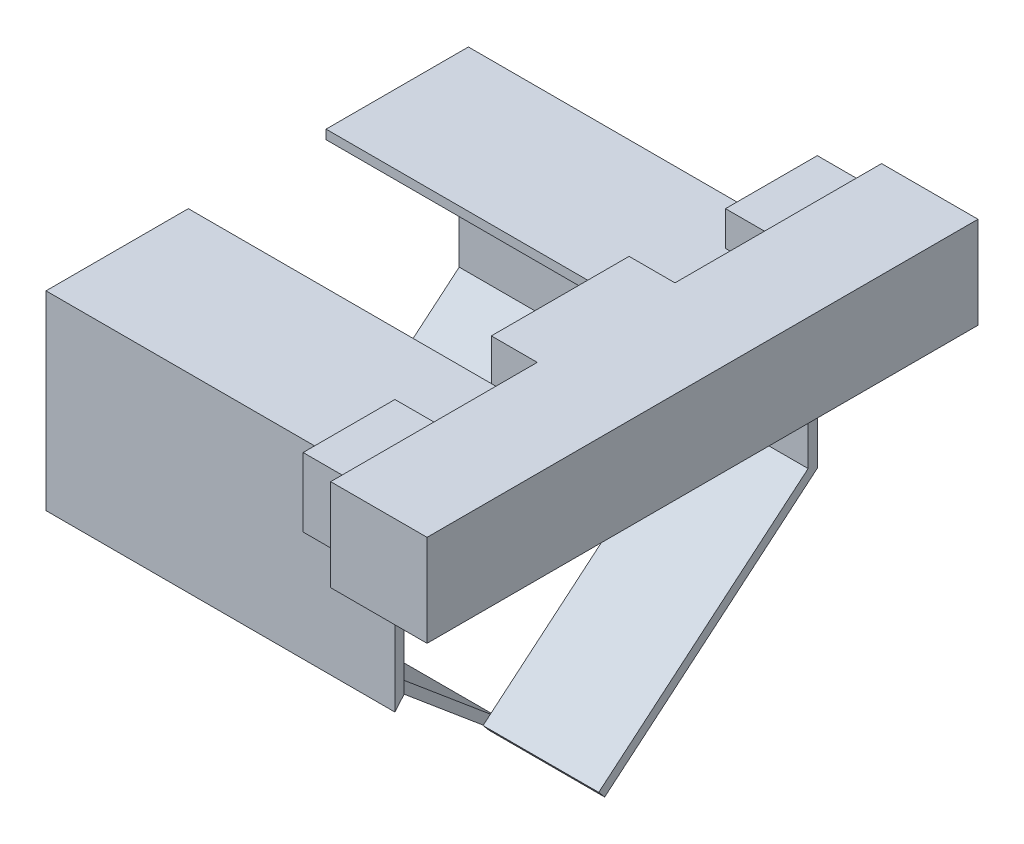
SolidWorks part; units mm, degrees
ref_plane "Front Plane" through (0, 0, 0) normal (0, 0, 1) x (1, 0, 0)
ref_plane "Top Plane" through (0, 0, 0) normal (0, 1, 0) x (1, 0, 0)
ref_plane "Right Plane" through (0, 0, 0) normal (1, 0, 0) x (0, 0, -1)
sketch "Sketch1" plane through (0, 0, 0) normal (1, 0, 0) x (0, 0, -1)
  line L0 (-19.05, 0) -> (19.05, 0) construction
  line L1 (19.05, 0) -> (57.15, 0)
  line L2 (57.15, 0) -> (57.15, -50.8)
  line L3 (57.15, -50.8) -> (-1.2226, -99.7804)
  line L4 (-19.05, 0) -> (-57.15, 0)
  line L5 (-57.15, 0) -> (-57.15, -50.8)
  line L6 (-57.15, -50.8) -> (1.2226, -99.7804)
  point P8 (0, 0)
  point P10 (0, 0)
  dimension "D1" = 38.1
  dimension "D2" = 50.8
  dimension "D3" = 76.2
  dimension "D4" = 130
  dimension "D5" = 130
extrude "Extrude-Thin4" add sketch "Sketch1" along normal blind 96.52 thin thin type mid plane wall 2.54
sketch "Sketch5" plane through (0, -58.9244, 49.4435) normal (0, -0.766, 0.6428) x (1, 0, 0)
  line L0 (96.52, -65.0742) -> (0, -65.0742) construction
  line L1 (0, 11.718) -> (32.004, 11.718)
  line L2 (0, 11.718) -> (0, -65.0742)
  line L3 (0, -65.0742) -> (32.004, -65.0742)
  line L4 (32.004, 11.718) -> (32.004, -65.0742)
  line L6 (96.52, 11.718) -> (64.516, 11.718)
  line L7 (96.52, 11.718) -> (96.52, -65.0742)
  line L8 (96.52, -65.0742) -> (64.516, -65.0742)
  line L9 (64.516, 11.718) -> (64.516, -65.0742)
  dimension "D1" = 32.004
extrude "Cut-Extrude2" cut sketch "Sketch5" against normal blind 26.67
sketch "Sketch6" plane through (0, -58.9244, -49.4435) normal (0, -0.766, -0.6428) x (1, 0, 0)
  line L0 (96.52, 65.0742) -> (0, 65.0742) construction
  line L1 (0, -11.718) -> (32.004, -11.718) construction
  line L2 (0, -11.718) -> (0, 65.0742) construction
  line L3 (0, 65.0742) -> (32.004, 65.0742) construction
  line L4 (32.004, -11.718) -> (32.004, 65.0742)
  line L6 (96.52, -11.718) -> (64.516, -11.718) construction
  line L7 (96.52, -11.718) -> (96.52, 65.0742) construction
  line L8 (96.52, 65.0742) -> (64.516, 65.0742) construction
  line L9 (64.516, -11.718) -> (64.516, 65.0742)
  line L10 (64.516, -11.718) -> (32.004, -11.718)
  line L11 (64.516, -11.718) -> (64.516, 65.0742)
  line L12 (64.516, 65.0742) -> (32.004, 65.0742)
  line L13 (32.004, -11.718) -> (32.004, 65.0742)
  line M10 (0, -11.718) -> (96.52, -11.718)
  line M12 (96.52, 65.0742) -> (0, 65.0742)
  dimension "D1" = 32.004
extrude "Cut-Extrude3" cut sketch "Sketch6" against normal blind 26.67 contours L9 L4 M10 M12
ref_plane "Left Plane" through (96.52, 0, 0) normal (1, 0, 0) x (0, 0, -1)
sketch "Sketch7" plane through (96.52, 0, 0) normal (1, 0, 0) x (0, 0, -1)
  line L1 (76.2, 12.7) -> (-76.2, 12.7)
  line L2 (76.2, 12.7) -> (76.2, -12.7)
  line L3 (76.2, -12.7) -> (-76.2, -12.7)
  line L4 (-76.2, 12.7) -> (-76.2, -12.7)
  line L5 (76.2, 12.7) -> (-76.2, -12.7) construction
  line L6 (76.2, -12.7) -> (-76.2, 12.7) construction
  point P0 (0, 0)
  dimension "D1" = 152.4
  dimension "D2" = 25.4
extrude "Boss-Extrude1" add sketch "Sketch7" along normal blind 26.67
sketch "Sketch8" plane through (96.52, 0, 0) normal (-1, 0, 0) x (0, 0, 1)
  line L0 (55.88, -12.7) -> (-55.88, -12.7) construction
  line L1 (19.05, 12.7) -> (-19.05, 12.7)
  line L2 (19.05, 12.7) -> (19.05, -12.7)
  line L3 (19.05, -12.7) -> (-19.05, -12.7)
  line L4 (-19.05, 12.7) -> (-19.05, -12.7)
  line L5 (19.05, 12.7) -> (-19.05, -12.7) construction
  line L6 (19.05, -12.7) -> (-19.05, 12.7) construction
  line L7 (-19.05, -1.27) -> (-19.05, 1.27) construction
  line L9 (0, 12.7) -> (0, -12.7)
  point P0 (0, 0)
  line M7 (-55.88, -12.7) -> (55.88, -12.7)
  line M10 (19.05, -1.27) -> (19.05, 1.27)
  line M15 (76.2, 12.7) -> (-76.2, 12.7)
  line M20 (-19.05, 1.27) -> (-19.05, -1.27)
extrude "Boss-Extrude2" add sketch "Sketch8" along normal blind 12.7 contours L9 L1 L4 M20 M7 | L9 L3 L2 M15 M10
sketch "Sketch9" plane through (83.82, 0, 0) normal (-1, 0, 0) x (0, 0, 1)
  line L0 (0, 0) -> (0, -12.7)
  line L1 (-19.05, -12.7) -> (19.05, -12.7) construction
  line L2 (0, -12.7) -> (0, 12.7)
  line L3 (19.05, 12.7) -> (-19.05, 12.7) construction
sketch "Sketch10" plane through (0, 12.7, 0) normal (0, 1, 0) x (1, 0, 0)
  line L0 (96.52, 19.05) -> (96.52, -19.05)
  line L1 (96.52, -62.3993) -> (96.52, 62.3993) construction
  line L2 (83.82, 19.05) -> (96.52, 19.05) construction
  line L3 (83.82, -19.05) -> (96.52, -19.05) construction
  line L4 (83.82, 0) -> (96.52, 0)
  line L5 (83.82, -19.05) -> (83.82, 19.05) construction
sketch "Sketch12" plane through (83.82, 0, 0) normal (-1, 0, 0) x (0, 0, 1)
  line L0 (0, -12.7) -> (-19.05, -12.7)
  line L1 (0, -12.7) -> (19.05, -12.7)
sketch "Sketch13" plane through (96.52, 0, 0) normal (-1, 0, 0) x (0, 0, 1)
  line L1 (-45.72, 10.795) -> (-71.12, 10.795)
  line L2 (-45.72, 10.795) -> (-45.72, -8.255)
  line L3 (-45.72, -8.255) -> (-71.12, -8.255)
  line L4 (-71.12, 10.795) -> (-71.12, -8.255)
  line L5 (-45.72, 10.795) -> (-71.12, -8.255) construction
  line L6 (-45.72, -8.255) -> (-71.12, 10.795) construction
  line L8 (0, -12.7) -> (-19.05, -12.7) construction
  line L9 (0, -12.7) -> (0, 12.7) construction
  line L11 (71.12, 10.795) -> (45.72, 10.795)
  line L12 (71.12, 10.795) -> (71.12, -8.255)
  line L13 (71.12, -8.255) -> (45.72, -8.255)
  line L14 (45.72, 10.795) -> (45.72, -8.255)
  line L15 (71.12, 10.795) -> (45.72, -8.255) construction
  line L16 (71.12, -8.255) -> (45.72, 10.795) construction
  point P0 (-58.42, 1.27)
  point P10 (58.42, 1.27)
extrude "Boss-Extrude3" add sketch "Sketch13" along normal blind 12.7
